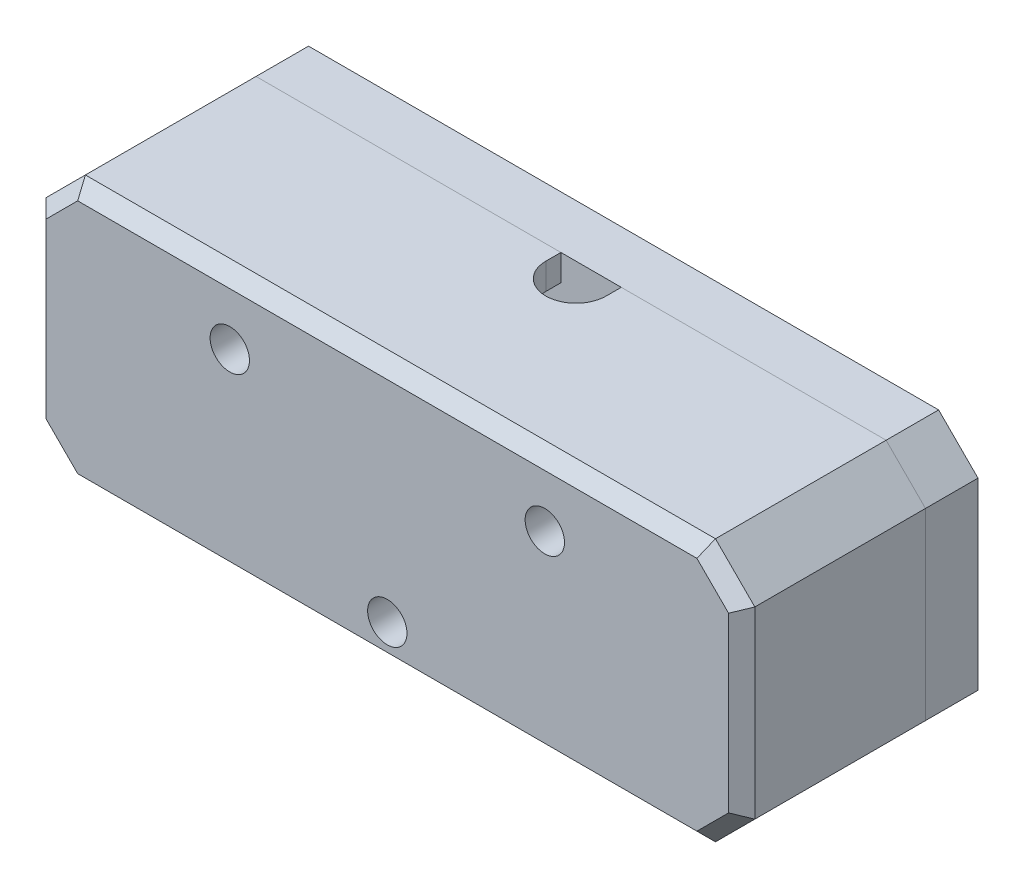
SolidWorks part; units mm, degrees
ref_plane "Front Plane" through (0, 0, 0) normal (0, 0, 1) x (1, 0, 0)
ref_plane "Top Plane" through (0, 0, 0) normal (0, 1, 0) x (1, 0, 0)
ref_plane "Right Plane" through (0, 0, 0) normal (1, 0, 0) x (0, 0, -1)
sketch "Sketch1" plane through (0, 0, 0) normal (0, 0, 1) x (1, 0, 0)
  point P0 (0, 0)
  line B0 (-58.375, 9.9) -> (-58.375, -9.9) construction
  line B1 (-58.375, -9.9) -> (-56.875, -9.9) construction
  line B2 (-56.875, 9.9) -> (-58.375, 9.9) construction
  line B3 (-56.875, -9.9) -> (-43.625, -9.9) construction
  line B4 (-43.625, -9.9) -> (-43.625, 9.9) construction
  line B5 (-43.625, 9.9) -> (-56.875, 9.9) construction
  line B6 (40.375, -9.8) -> (43.875, -9.8) construction
  line B7 (43.875, -9.8) -> (43.875, 9.8) construction
  line B8 (43.875, 9.8) -> (40.375, 9.8) construction
  line B9 (-40.375, 9.8) -> (-40.375, -9.8) construction
  line B10 (-40.375, -9.8) -> (40.375, -9.8) construction
  line B11 (40.375, 9.8) -> (-40.375, 9.8) construction
  line B12 (0, 9.8) -> (0, -9.8) construction
  circle B13 centre (18.475, 0) radius 2.1 construction
  circle B14 centre (-21.525, 0) radius 2.1 construction
sketch_block_instance "Block1-1"
sketch_block "Block1"
ref_plane "Plane1" through (0, 9.8, 0) normal (0, 1, 0) x (-1, 0, 0)
sketch "Sketch2" plane through (0, 9.8, 0) normal (0, 1, 0) x (-1, 0, 0)
  line B0 (-40.375, -100.55) -> (40.375, -100.55) construction
  line B1 (40.375, -100.55) -> (40.375, -80.7916) construction
  line B2 (40.375, -19.7584) -> (40.375, 0) construction
  line B3 (40.375, 0) -> (-40.375, 0) construction
  line B4 (-43.775, -3.4) -> (-43.775, -97.15) construction
  line B5 (43.725, -72.276) -> (43.725, -100.55) construction
  line B6 (43.725, -100.55) -> (56.875, -100.55) construction
  line B7 (58.275, -99.15) -> (58.275, -1.4) construction
  line B8 (56.875, 0) -> (43.725, 0) construction
  line B9 (43.725, 0) -> (43.725, -28.274) construction
  arc B10 (-43.775, -97.15) -> (-40.375, -100.55) centre (-40.375, -97.15) ccw construction
  arc B11 (40.375, -80.7916) -> (37.5951, -79.5891) centre (38.725, -80.7916) ccw construction
  arc B12 (37.5951, -20.9609) -> (37.5951, -79.5891) centre (10.05, -50.275) ccw construction
  arc B13 (37.5951, -20.9609) -> (40.375, -19.7584) centre (38.725, -19.7584) ccw construction
  arc B14 (-40.375, 0) -> (-43.775, -3.4) centre (-40.375, -3.4) ccw construction
  arc B15 (43.725, -72.276) -> (43.725, -28.274) centre (10.05, -50.275) ccw construction
  arc B16 (56.875, -100.55) -> (58.275, -99.15) centre (56.875, -99.15) ccw construction
  arc B17 (58.275, -1.4) -> (56.875, 0) centre (56.875, -1.4) ccw construction
  circle B18 centre (-33.475, -80.275) radius 2.1 construction
  circle B19 centre (-33.475, -70.275) radius 2.1 construction
  circle B20 centre (-33.475, -30.275) radius 2.1 construction
  circle B21 centre (-33.475, -20.275) radius 2.1 construction
sketch_block_instance "Block2-1"
sketch_block "Block2"
sketch "Sketch3" plane through (0, 0, 0) normal (0, 0, 1) x (1, 0, 0)
  line L0 (-21.525, 0) -> (-21.525, -9.8) construction
  line L1 (-28.525, 10) -> (25.475, 10)
  line L2 (-28.525, 10) -> (-28.525, -10)
  line L3 (-28.525, -10) -> (25.475, -10)
  line L4 (25.475, 10) -> (25.475, -10)
  line L5 (-1.525, -10) -> (-1.525, 10) construction
  line L6 (-28.525, 0) -> (25.475, 0) construction
  line L7 (-40.375, -9.8) -> (40.375, -9.8) construction
  line L8 (18.475, 0) -> (18.475, -9.8) construction
  line L9 (-21.525, -4.9) -> (18.475, -4.9) construction
  circle A0 centre (-21.525, 0) radius 2.6
  circle A1 centre (18.475, 0) radius 2.6
  circle A2 centre (-21.525, 0) radius 5 construction
  circle A3 centre (18.475, 0) radius 5 construction
  point P14 (-1.525, -4.9)
  point P156 (0, 0)
  dimension "D3" = 5.2
  dimension "D4" = 10
  dimension "D1" = 54
  dimension "D2" = 20
extrude "Boss-Extrude1" add sketch "Sketch3" along normal blind 4
sketch "Sketch4" plane through (0, 0, 4) normal (0, 0, 1) x (1, 0, 0)
  line L5 (25.475, 10) -> (-28.525, 10) construction
  line L6 (-16.525, -4) -> (13.475, -4)
  line L7 (-16.525, -4) -> (-16.525, -10)
  line L8 (-16.525, -10) -> (13.475, -10)
  line L9 (13.475, -4) -> (13.475, -10)
  line L10 (-1.525, -10) -> (-1.525, -4) construction
  line L11 (-16.525, -7) -> (13.475, -7) construction
  line L14 (-28.525, -10) -> (25.475, -10) construction
  point P0 (-1.525, -7)
  point P6 (-1.525, 10)
  dimension "D2" = 6
  dimension "D3" = 30
extrude "Boss-Extrude2" add sketch "Sketch4" along normal blind 11
sketch "Sketch5" plane through (0, -10, 0) normal (0, -1, 0) x (1, 0, 0)
  line L0 (-16.525, 8.5) -> (13.475, 8.5) construction
  line L3 (-1.525, 8.5) -> (-1.525, 15) construction
  line L4 (-16.525, 15) -> (13.475, 15) construction
  circle A0 centre (-9.025, 8.5) radius 1.5
  circle A1 centre (5.975, 8.5) radius 1.5
  circle A2 centre (-9.025, 8.5) radius 6.105 construction
  circle A3 centre (5.975, 8.5) radius 6.105 construction
  dimension "D1" = 3
  dimension "D2" = 15
  dimension "D3" = 12.21
  dimension "D4" = 6.5
extrude "Cut-Extrude1" cut sketch "Sketch5" against normal up to surface (6 mm away) up to face at (-1.525, -4, 9.5)
sketch "Sketch6" plane through (0, -4, 0) normal (0, 1, 0) x (1, 0, 0)
  line L1 (-9.025, -5.3534) -> (-11.75, -6.9267)
  line L2 (-11.75, -6.9267) -> (-11.75, -10.0733)
  line L3 (-11.75, -10.0733) -> (-9.025, -11.6466)
  line L4 (-9.025, -11.6466) -> (-6.3, -10.0733)
  line L5 (-6.3, -10.0733) -> (-6.3, -6.9267)
  line L6 (-6.3, -6.9267) -> (-9.025, -5.3534)
  line L7 (5.975, -5.3534) -> (3.25, -6.9267)
  line L8 (3.25, -6.9267) -> (3.25, -10.0733)
  line L9 (3.25, -10.0733) -> (5.975, -11.6466)
  line L10 (5.975, -11.6466) -> (8.7, -10.0733)
  line L11 (8.7, -10.0733) -> (8.7, -6.9267)
  line L12 (8.7, -6.9267) -> (5.975, -5.3534)
  circle A0 centre (-9.025, -8.5) radius 2.725 construction
  circle A1 centre (5.975, -8.5) radius 2.725 construction
  dimension "D1" = 5.45
extrude "Cut-Extrude2" cut sketch "Sketch6" against normal blind 2
chamfer "Chamfer1" distance 3 angle 45 4 edges at (-28.525, -10, 2) (-28.525, 10, 2) (25.475, -10, 2) (25.475, 10, 2)
sketch "Sketch9" plane through (0, 0, 4) normal (0, 0, 1) x (1, 0, 0)
  line L0 (22.475, -10) -> (13.675, -10)
  line L1 (22.475, -10) -> (25.475, -7)
  line L2 (25.475, -7) -> (25.475, 7)
  line L3 (25.475, 7) -> (22.475, 10)
  line L4 (22.475, 10) -> (-25.525, 10)
  line L5 (-25.525, 10) -> (-28.525, 7)
  line L6 (-28.525, 7) -> (-28.525, -7)
  line L7 (-28.525, -7) -> (-25.525, -10)
  line L8 (-25.525, -10) -> (-16.725, -10)
  line L9 (-28.525, -10) -> (25.475, -10) construction
  line L10 (13.475, -10) -> (13.475, -4) construction
  line L11 (-16.525, -4) -> (-16.525, -10) construction
  line L12 (21.6466, -8) -> (13.675, -8)
  line L13 (21.6466, -8) -> (23.475, -6.1716)
  line L14 (23.475, -6.1716) -> (23.475, 6.1716)
  line L15 (23.475, 6.1716) -> (21.6466, 8)
  line L16 (21.6466, 8) -> (-24.6966, 8)
  line L17 (-24.6966, 8) -> (-26.525, 6.1716)
  line L18 (-26.525, 6.1716) -> (-26.525, -6.1716)
  line L19 (-26.525, -6.1716) -> (-24.6966, -8)
  line L20 (-24.6966, -8) -> (-16.725, -8)
  line L21 (-16.725, -10) -> (-16.725, -8)
  line L22 (13.675, -10) -> (13.675, -8)
  dimension "D1" = 0.2
  dimension "D2" = 0.2
  dimension "D3" = 2
extrude "Boss-Extrude3" add sketch "Sketch9" along normal up to surface (11 mm away) separate body up to face at (-1.525, -7, 15)
sketch "Sketch10" plane through (0, 0, 15) normal (0, 0, 1) x (1, 0, 0)
  line L0 (-25.525, -10) -> (22.475, -10)
  line L1 (22.475, -10) -> (25.475, -7)
  line L2 (25.475, -7) -> (25.475, 7)
  line L3 (25.475, 7) -> (22.475, 10)
  line L4 (22.475, 10) -> (-25.525, 10)
  line L5 (-25.525, 10) -> (-28.525, 7)
  line L6 (-28.525, 7) -> (-28.525, -7)
  line L7 (-28.525, -7) -> (-25.525, -10)
extrude "Boss-Extrude4" add sketch "Sketch10" along normal blind 3
sketch "Sketch11" plane through (0, 0, 18) normal (0, 0, 1) x (1, 0, 0)
  line L0 (-1.525, -4) -> (-1.525, -10) construction
  line L1 (13.475, -4) -> (-16.525, -4) construction
  line L2 (-25.525, -10) -> (22.475, -10) construction
  line L4 (-24.6966, 8) -> (21.6466, 8) construction
  circle A0 centre (-1.525, -7) radius 1.5
  circle A1 centre (-13.525, 5) radius 1.5
  circle A2 centre (10.475, 5) radius 1.5
  dimension "D1" = 24
  dimension "D2" = 3
  dimension "D3" = 3
extrude "Cut-Extrude3" cut sketch "Sketch11" against normal up to surface (3 mm away) up to face at (-1.525, -3, 15)
sketch "Sketch12" plane through (0, 0, 15) normal (0, 0, -1) x (-1, 0, 0)
  line L1 (10.025, 5) -> (10.025, 8)
  line L2 (24.6966, 8) -> (-21.6466, 8) construction
  line L3 (10.025, 8) -> (17.025, 8)
  line L4 (17.025, 5) -> (17.025, 8)
  line L5 (-13.975, 5) -> (-13.975, 8)
  line L6 (-13.975, 8) -> (-6.975, 8)
  line L7 (-6.975, 8) -> (-6.975, 5)
  circle A2 centre (-10.475, 5) radius 3.5
  arc A3 (-13.975, 5) -> (-6.975, 5) centre (-10.475, 5) ccw
  circle A5 centre (13.525, 5) radius 3.5
  arc A6 (10.025, 5) -> (17.025, 5) centre (13.525, 5) ccw
  dimension "D1" = 2
  dimension "D2" = 2
extrude "Boss-Extrude5" add sketch "Sketch12" along normal up to surface (11 mm away) up to face at (-1.525, -2.3333, 4)
sketch "Sketch13" plane through (0, 0, 15) normal (0, 0, 1) x (1, 0, 0)
  circle A0 centre (-13.525, 5) radius 1.375
  circle A1 centre (10.475, 5) radius 1.375
  circle A2 centre (-1.525, -7) radius 1.375
  dimension "D1" = 2.75
extrude "Cut-Extrude4" cut sketch "Sketch13" against normal blind 8
chamfer "Chamfer2" distance 1 angle 45 8 edges at (-1.525, -10, 18) (23.975, -8.5, 18) (25.475, 0, 18) (23.975, 8.5, 18) (-1.525, 10, 18) (-27.025, 8.5, 18) (-28.525, 0, 18) (-27.025, -8.5, 18)
sketch "Sketch14" plane through (0, 10, 0) normal (0, 1, 0) x (1, 0, 0)
  line L0 (-2.3, -5.15) -> (-2.3, -4)
  line L1 (-2.3, -4) -> (2.3, -4)
  line L2 (2.3, -4) -> (2.3, -5.15)
  line L3 (22.475, -4) -> (-25.525, -4) construction
  arc A0 (-2.3, -5.15) -> (2.3, -5.15) centre (0, -5.15) ccw
  dimension "D1" = 2.3
  dimension "D2" = 1.15
extrude "Cut-Extrude5" cut sketch "Sketch14" against normal up to surface (2 mm away) up to face at (-1.525, 8, 9.5)
equation "\"D2@Sketch14\"=\"D1@Sketch14\"/2"
